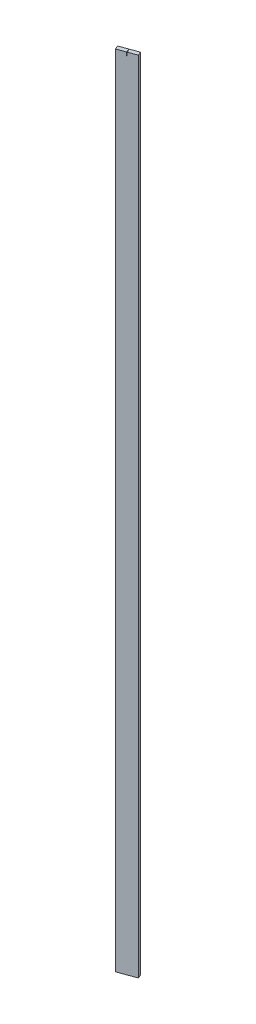
SolidWorks part; units mm, degrees
ref_plane "Front" through (0, 0, 0) normal (0, 0, 1) x (1, 0, 0)
ref_plane "Top" through (0, 0, 0) normal (0, 1, 0) x (1, 0, 0)
ref_plane "Right" through (0, 0, 0) normal (1, 0, 0) x (0, 0, -1)
sketch "草图1" plane through (915.5055, 0, 2515.3306) normal (-0.342, 0, -0.9397) x (-0.9397, 0, 0.342)
  line L0 (-104.7387, 56.2685) -> (-104.7387, -1943.7315)
  line L1 (-104.7387, -1943.7315) -> (-59.9387, -1943.7315)
  line L2 (-59.9387, -1943.7315) -> (-59.9387, 56.2685)
  line L3 (-59.9387, 56.2685) -> (-104.7387, 56.2685)
  dimension "D1" = 2000
extrude "凸台-拉伸1" add sketch "草图1" against normal blind 10
sketch "草图2" plane through (56.3239, 0, -20.5002) normal (-0.9397, 0, 0.342) x (0.342, 0, 0.9397)
  line L0 (2676.7589, 49.6534) -> (2686.7589, 49.6534)
  line L3 (2676.7589, -1943.7315) -> (2676.7589, 56.2685) construction
  line L4 (2686.7589, -1943.7315) -> (2686.7589, 56.2685) construction
  line L5 (2678.7337, 49.6534) -> (2678.7337, 56.2685)
  line L6 (2686.7589, 56.2685) -> (2676.7589, 56.2685) construction
  line L7 (2678.7337, 56.2685) -> (2684.7842, 56.2685)
  line L8 (2684.7842, 56.2685) -> (2684.7826, 49.75)
  arc A1 (2678.7337, 49.6534) -> (2684.7826, 49.75) centre (2681.7589, 49.6534) ccw
  line M4 (2686.7589, 56.2685) -> (2676.7589, 56.2685)
extrude "切除-拉伸2" cut sketch "草图2" against normal through all contours L0 A1 L8 L5 M4 | L0 A1
sketch "草图3" plane through (56.3239, 0, -20.5002) normal (-0.9397, 0, 0.342) x (0.342, 0, 0.9397)
  line L0 (2678.7337, 49.6534) -> (2678.7337, 56.2685)
  line L1 (2678.7337, 56.2685) -> (2684.7842, 56.2685)
  line L2 (2684.7842, 56.2685) -> (2684.7842, 49.6534)
  arc A0 (2678.7337, 49.6534) -> (2684.7826, 49.75) centre (2681.7589, 49.6534) ccw construction
  arc A1 (2678.7337, 49.6534) -> (2684.7842, 49.6534) centre (2681.7589, 49.6534) ccw
extrude "凸台-拉伸2" add sketch "草图3" against normal blind 44.8
sketch "草图4" plane through (0, 56.2685, 0) normal (0, 1, 0) x (1, 0, 0)
  line L0 (996.2987, -2496.5661) -> (992.8785, -2487.1691)
  line L1 (975.2496, -2504.2273) -> (1017.3478, -2488.9048) construction
  line L2 (971.8294, -2494.8304) -> (1013.9276, -2479.5079) construction
  line L3 (992.8785, -2487.1691) -> (993.3484, -2486.9981)
  line L4 (992.8785, -2487.1691) -> (992.4087, -2487.3402)
  line L5 (993.3484, -2486.9981) -> (996.7837, -2496.4366)
  line L6 (992.4087, -2487.3402) -> (995.8289, -2496.7371)
  line L7 (995.8289, -2496.7371) -> (996.7837, -2496.4366)
  line M4 (1013.9276, -2479.5079) -> (971.8294, -2494.8304)
  line M6 (975.2496, -2504.2273) -> (1017.3478, -2488.9048)
  dimension "D1" = 0.5
  dimension "D2" = 0.5
extrude "切除-拉伸3" cut sketch "草图4" against normal blind 8.96 contours L6 L0 M4 M6 | L5 L0 M4 M6
